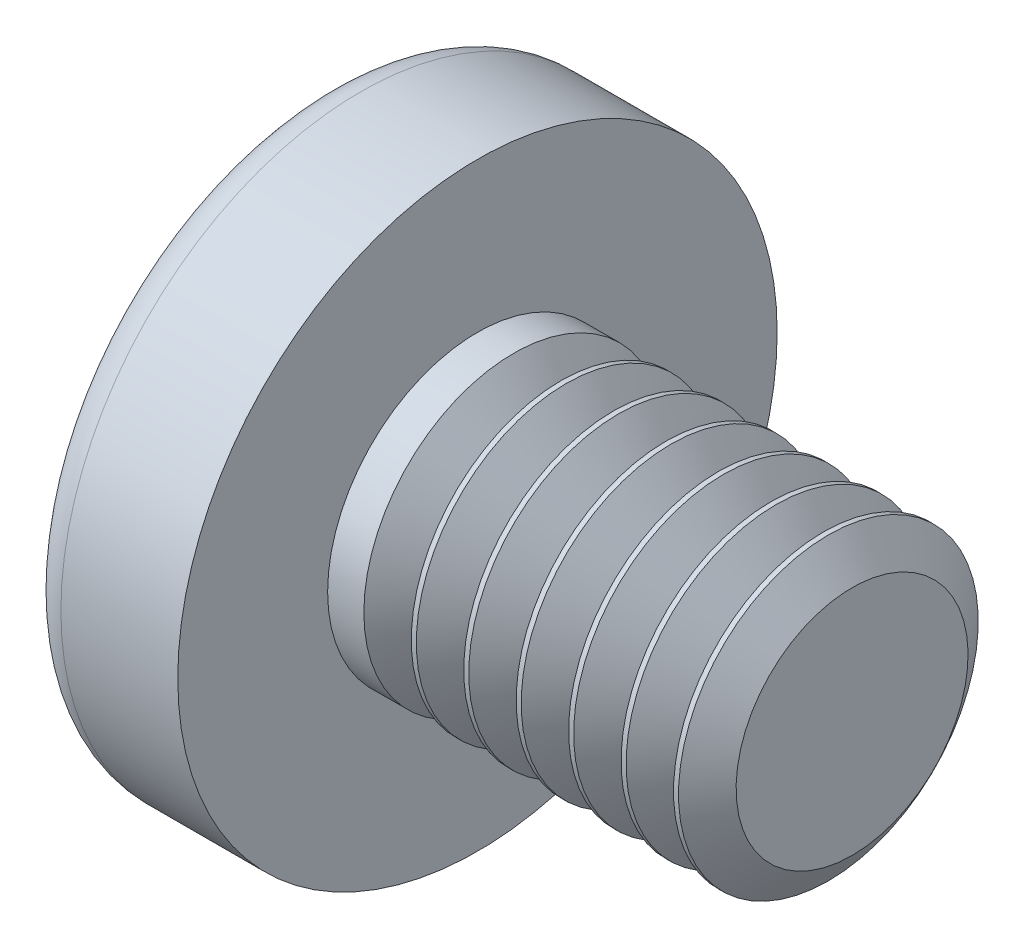
SolidWorks part; units mm, degrees
ref_plane "Plane1" through (0, 0, 0) normal (0, 0, 1) x (1, 0, 0)
ref_plane "Plane2" through (0, 0, 0) normal (0, 1, 0) x (1, 0, 0)
ref_plane "Plane3" through (0, 0, 0) normal (1, 0, 0) x (0, 0, -1)
other "Configuration Table"
sketch "BodySke" plane through (0, 0, 0) normal (0, 0, 1) x (1, 0, 0)
  line L0 (1.6, 1) -> (1.6, 2)
  line L1 (2, 6.35) -> (2, -3.175) construction
  line L2 (-25.4, 0) -> (127, 0) construction
  line L3 (4.1, 0) -> (0, 0)
  line L4 (1.6, 1) -> (4.1, 1)
  line L5 (4.1, 1) -> (4.1, 0)
  line L6 (0.8201, 2) -> (1.6, 2)
  line L7 (1.6, -1) -> (4.1, -1) construction
  line L8 (1.6, 6.35) -> (1.6, -3.175) construction
  arc A0 (0.6271, 1.9027) -> (0, 0) centre (3.2, 0) ccw
  arc A2 (0.6271, 1.9027) -> (0.8201, 2) centre (0.8201, 1.76) cw
  dimension "Head_crown_rad" = 3.2
  dimension "Head_fillet_rad" = 0.24
  dimension "Diameter" = 2
  dimension "Length" = 2.5
  dimension "Head_ht" = 1.6
  dimension "Head_dia" = 4
  dimension "Advance" = 0.4
  dimension "Thread_nom" = 2.5
revolve "Base-Revolve" add sketch "BodySke" angle 360 about L2
cosmetic thread "ThreadCosmetic" [suppressed] parameters "Thread_length"=2.1, "Thread_minor"=1.548
sketch "Sketch3" plane through (0, 0, 0) normal (1, 0, 0) x (0, 0, -1)
  line L0 (0.24, -0.91) -> (-0.24, -0.91)
  line L1 (0.24, -0.91) -> (0.24, 0.91)
  line L2 (-0.24, 0.91) -> (0.24, 0.91)
  line L3 (-0.24, 0.91) -> (-0.24, -0.91)
  dimension "Cross_dia" = 1.82
  dimension "D1" = 0.91
  dimension "Cross_width" = 0.48
  dimension "D2" = 0.24
ref_plane "Plane4" through (1.19, 0, 0) normal (1, 0, 0) x (0, 0, -1)
sketch "Sketch4" plane through (1.19, 0, 0) normal (1, 0, 0) x (0, 0, -1)
  line L0 (0.12, -0.12) -> (-0.12, -0.12)
  line L1 (0.12, -0.12) -> (0.12, 0.12)
  line L2 (-0.12, 0.12) -> (0.12, 0.12)
  line L3 (-0.12, 0.12) -> (-0.12, -0.12)
  dimension "D2" = 0.24
  dimension "D1" = 0.24
  dimension "D3" = 0.12
  dimension "D4" = 0.12
loft "Cut-Loft1" cut profiles "Sketch3", "Sketch4"
pattern_circular "CirPattern1" count 2 every 90 about axis through (0, 0, 0) along (1, 0, 0) of "Cut-Loft1"
sketch "ThdSchSke" plane through (0, 0, 0) normal (0, 0, 1) x (1, 0, 0)
  line L0 (2, -0.774) -> (1.8418, -1)
  line L1 (2, -0.774) -> (2.1582, -1)
  line L2 (2.1582, -1) -> (2.1582, -1.25)
  line L3 (-3.175, 0) -> (5.1513, 0) construction
  line L5 (2.1582, -1.25) -> (1.8418, -1.25)
  line L6 (1.8418, -1.25) -> (1.8418, -1)
  dimension "Diameter" = 2
  dimension "SideAngle" = 55
  dimension "VeeAngle" = 70
  dimension "Thread_minor" = 1.548
  dimension "Overcut" = 2.5
  dimension "Start" = 2
revolve "ThreadSchematic" cut sketch "ThdSchSke" angle 360 about L3
pattern_linear "ThdSchPat" count 7 spacing 0.35 along (1, 0, 0) of "ThreadSchematic"
equation "\"D1@Sketch3\" = \"Cross_dia@Sketch3\" / 2"
equation "\"D2@Sketch3\" = \"Cross_width@Sketch3\" / 2"
equation "\"D1@Sketch4\" = \"Cross_width@Sketch3\" *.5"
equation "\"D2@Sketch4\" = \"D1@Sketch4\""
equation "\"D3@Sketch4\" = \"D1@Sketch4\" / 2"
equation "\"D4@Sketch4\" = \"D2@Sketch4\" / 2"
equation "\"Thread_length@ThreadCosmetic\" = ((sgn( (\"Length@BodySke\" - \"Advance@BodySke\" ) - \"Thread_nom@BodySke\" )-1)*( (\"Length@BodySke\" - \"Advance@BodySke\" ) - \"Thread_nom@BodySke\" ))/-2+ \"Thread_nom@BodySke\""
equation "\"Thread_minor@ThdSchSke\" = \"Thread_minor@ThreadCosmetic\""
equation "\"Diameter@ThdSchSke\" = \"Diameter@BodySke\""
equation "\"Overcut@ThdSchSke\" = \"Diameter@BodySke\" * 1.25"
equation "\"Start@ThdSchSke\" = \"Head_ht@BodySke\" + \"Length@BodySke\" - \"Thread_length@ThreadCosmetic\"  '---Non-countersunk---"
equation "\"Num_threads@ThdSchPat\" = int( \"Thread_length@ThreadCosmetic\" / \"Advance@BodySke\" + 0.999 )  + 1"
equation "\"Advance@ThdSchPat\" = \"Thread_length@ThreadCosmetic\" /  (\"Num_threads@ThdSchPat\" - 1) 'relax it"
